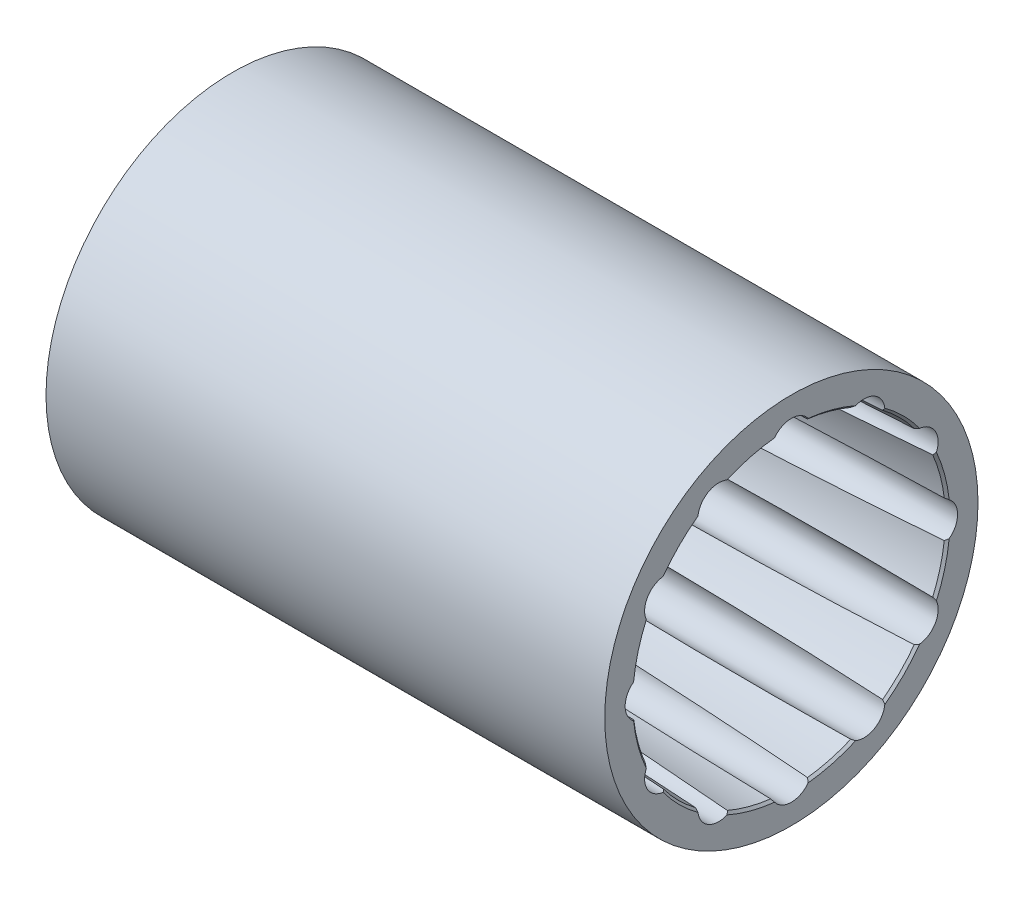
SolidWorks part; units mm, degrees
material "AISI 4340 Steel, normalized"
ref_plane "Front" through (0, 0, 0) normal (0, 0, 1) x (1, 0, 0)
ref_plane "Top" through (0, 0, 0) normal (0, 1, 0) x (1, 0, 0)
ref_plane "Right" through (0, 0, 0) normal (1, 0, 0) x (0, 0, -1)
sketch "Sketch1" plane through (0, 0, 0) normal (1, 0, 0) x (0, 0, -1)
  circle A0 centre (0, 0) radius 21.209
extrude "Extrude1" add sketch "Sketch1" along normal blind 63.5
sketch "Sketch2" plane through (63.5, 0, 0) normal (1, 0, 0) x (0, 0, -1)
  circle A0 centre (0, 0) radius 17.78
extrude "Extrude2" cut sketch "Sketch2" against normal blind 25.4 draft 2.87
sketch "Sketch3" plane through (63.5, 0, 0) normal (1, 0, 0) x (0, 0, -1)
  point P0 (-16.51, 0)
hole_wizard "3/16 (0.1875) Diameter Hole1" positions "3DSketch1" profile "Sketch4" hole size "3/16" standard "Ansi Inch"
sketch3d "3DSketch1"
  point P0 (63.5, 0, 16.51)
sketch "Sketch4" plane through (63.5, 0, 16.51) normal (0, 1, 0) x (0, 0, -1)
  line L0 (0, 0) -> (0, 33.1808)
  line L1 (0, 33.1808) -> (2.3812, 31.75)
  line L2 (2.3812, 31.75) -> (2.3812, 0)
  line L5 (2.3812, 0) -> (0, 0)
  line L10 (0, 33.1808) -> (-2.3812, 31.75) construction
  line L11 (0, -6.35) -> (0, 107.95) construction
  dimension "Hole Dia." = 4.7625
  dimension "Hole Depth" = 31.75
  dimension "Drill Angle" = 118
pattern_circular "CirPattern1" count 12 over 360 about axis through (0, 0, 0) along (1, 0, 0) of "3/16 (0.1875) Diameter Hole1"
chamfer "Chamfer2" distance 0.254 angle 45 12 edges at (63.5, 17.1742, -4.6018) (63.5, 12.5724, -12.5724) (63.5, 4.6018, -17.1742) (63.5, -4.6018, -17.1742) (63.5, -12.5724, -12.5724) (63.5, -17.1742, -4.6018) (63.5, -17.1742, 4.6018) (63.5, -12.5724, 12.5724) (63.5, -4.6018, 17.1742) (63.5, 4.6018, 17.1742) (63.5, 12.5724, 12.5724) (63.5, 17.1742, 4.6018)
